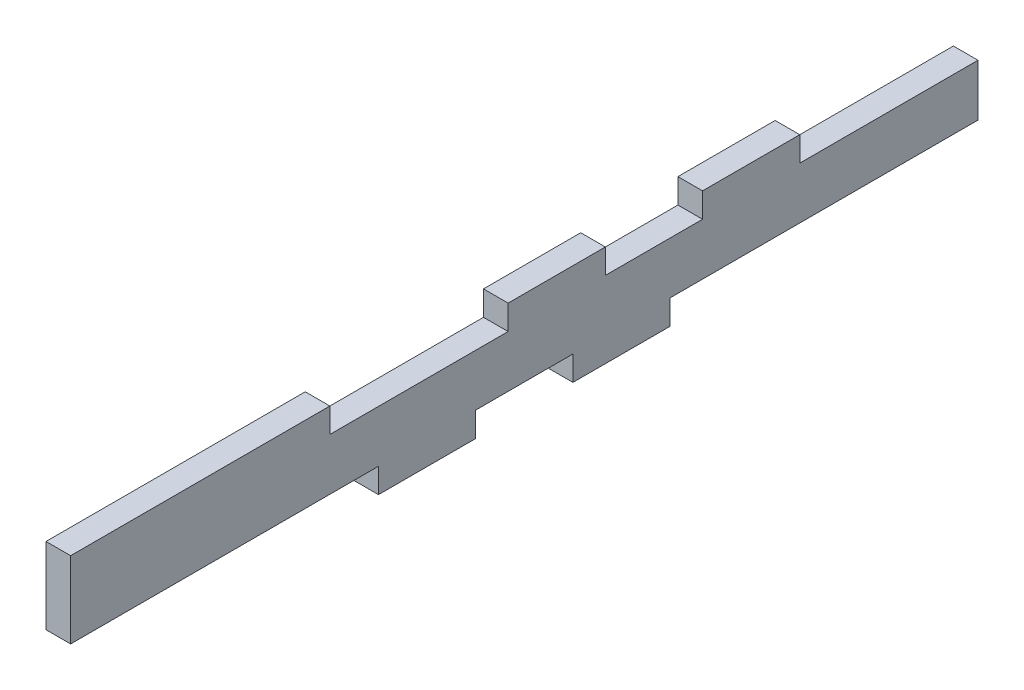
SolidWorks part; units mm, degrees
ref_plane "Front Plane" through (0, 0, 0) normal (0, 0, 1) x (1, 0, 0)
ref_plane "Top Plane" through (0, 0, 0) normal (0, 1, 0) x (1, 0, 0)
ref_plane "Right Plane" through (0, 0, 0) normal (1, 0, 0) x (0, 0, -1)
sketch "Sketch1" plane through (0, 0, 0) normal (1, 0, 0) x (0, 0, -1)
  line L1 (0, 0) -> (177.8, 0)
  line L2 (0, 0) -> (0, 19.812)
  line L3 (0, 19.812) -> (177.8, 19.812)
  line L4 (177.8, 0) -> (177.8, 19.812)
  dimension "D1" = 177.8
  dimension "D2" = 19.812
extrude "Base" add sketch "Sketch1" along normal blind 4.826
sketch "Sketch2" plane through (4.826, 0, 0) normal (1, 0, 0) x (0, 0, -1)
  line L0 (177.8, 19.812) -> (0, 19.812) construction
  line L2 (50.8, 19.812) -> (85.725, 19.812)
  line L3 (50.8, 19.812) -> (50.8, 14.986)
  line L4 (50.8, 14.986) -> (85.725, 14.986)
  line L5 (104.775, 19.812) -> (123.825, 19.812)
  line L6 (104.775, 19.812) -> (104.775, 14.986)
  line L7 (104.775, 14.986) -> (123.825, 14.986)
  line L8 (123.825, 19.812) -> (123.825, 14.986)
  line L9 (85.725, 14.986) -> (104.775, 14.986) construction
  line L10 (177.8, 19.812) -> (142.875, 19.812)
  line L11 (177.8, 19.812) -> (177.8, 14.986)
  line L12 (177.8, 14.986) -> (142.875, 14.986)
  line L13 (142.875, 19.812) -> (142.875, 14.986)
  line L14 (123.825, 14.986) -> (142.875, 14.986) construction
  line L15 (85.725, 19.812) -> (85.725, 14.986)
  line L16 (0, 19.812) -> (0, 0) construction
  point P20 (0, 9.906)
  dimension "D1" = 19.05
  dimension "D2" = 50.8
extrude "Top Tabs" cut sketch "Sketch2" against normal through all
sketch "Sketch3" plane through (4.826, 0, 0) normal (1, 0, 0) x (0, 0, -1)
  line L0 (0, 0) -> (177.8, 0) construction
  line L1 (0, 0) -> (60.325, 0)
  line L2 (0, 0) -> (0, 4.826)
  line L3 (0, 4.826) -> (60.325, 4.826)
  line L4 (60.325, 0) -> (60.325, 4.826)
  line L5 (177.8, 0) -> (117.475, 0)
  line L6 (177.8, 0) -> (177.8, 4.826)
  line L7 (177.8, 4.826) -> (117.475, 4.826)
  line L8 (117.475, 0) -> (117.475, 4.826)
  line L9 (98.425, 0) -> (79.375, 0)
  line L10 (98.425, 0) -> (98.425, 4.826)
  line L11 (98.425, 4.826) -> (79.375, 4.826)
  line L12 (79.375, 0) -> (79.375, 4.826)
  line L13 (60.325, 4.826) -> (79.375, 4.826) construction
  line L14 (98.425, 4.826) -> (117.475, 4.826) construction
  dimension "D1" = 19.05
  dimension "D2" = 4.826
extrude "Cut-Extrude2" cut sketch "Sketch3" against normal through all
equation "\"material\"= \"gmaterial@Forklift_v2.assembly\""
equation "\"tab\"= \"gtab@Forklift_v2.assembly\""
equation "\"D2@Sketch1\"=0.4+2*\"material\""
equation "\"D1@Base\"=\"material\""
equation "\"D1@Sketch2\"=\"tab\""
equation "\"D1@Sketch3\"=\"tab\""
equation "\"D2@Sketch3\"=\"material\""
